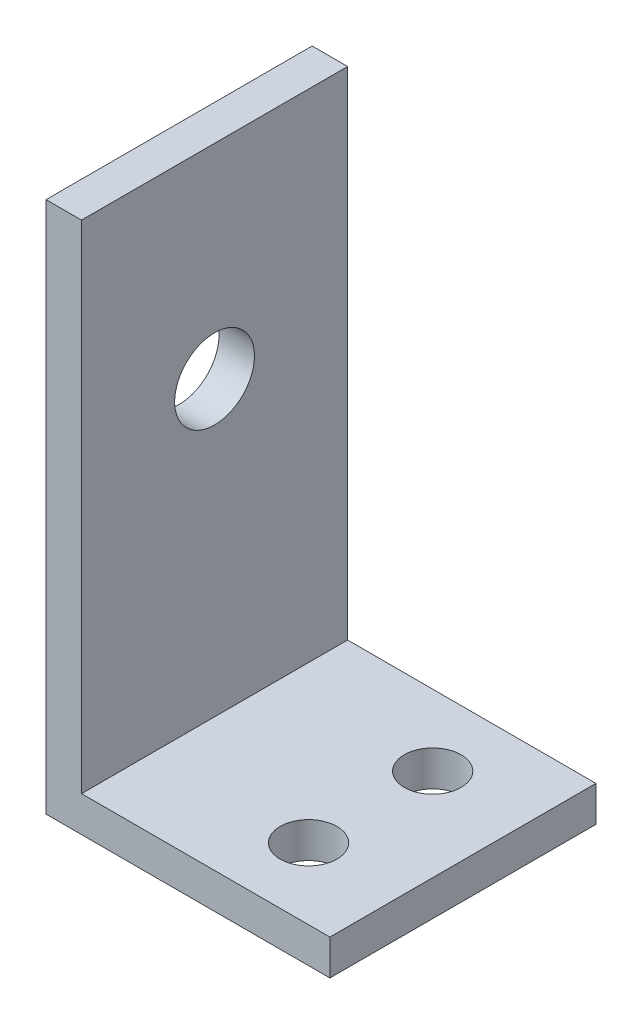
SolidWorks part; units mm, degrees
ref_plane "Front Plane" through (0, 0, 0) normal (0, 0, 1) x (1, 0, 0)
ref_plane "Top Plane" through (0, 0, 0) normal (0, 1, 0) x (1, 0, 0)
ref_plane "Right Plane" through (0, 0, 0) normal (1, 0, 0) x (0, 0, -1)
sketch "Sketch1" plane through (0, 0, 0) normal (0, 1, 0) x (1, 0, 0)
  line L1 (-3.8235, 10.0882) -> (12.1765, 10.0882)
  line L2 (-3.8235, 10.0882) -> (-3.8235, -4.9118)
  line L3 (-3.8235, -4.9118) -> (12.1765, -4.9118)
  line L4 (12.1765, 10.0882) -> (12.1765, -4.9118)
  dimension "D1" = 16
  dimension "D2" = 15
extrude "Boss-Extrude1" add sketch "Sketch1" along normal blind 2
sketch "Sketch4" plane through (0, 2, 0) normal (0, 1, 0) x (1, 0, 0)
  line L0 (12.1765, 10.0882) -> (-3.8235, 10.0882) construction
  line L1 (-3.8235, -4.9118) -> (-1.8235, -4.9118)
  line L2 (-3.8235, -4.9118) -> (-3.8235, 10.0882)
  line L3 (-3.8235, 10.0882) -> (-1.8235, 10.0882)
  line L4 (-1.8235, -4.9118) -> (-1.8235, 10.0882)
  dimension "D1" = 2
extrude "Boss-Extrude4" add sketch "Sketch4" along normal blind 28
hole_wizard "Ø3.2 (3.2) Diameter Slot1" positions "Sketch9" profile "Sketch7" size "Ø3.2" standard "ANSI Metric" slot yes end condition through all
sketch "Sketch9" plane through (0, 2, 0) normal (0, 1, 0) x (1, 0, 0)
  line L1 (12.1765, 10.0882) -> (-1.8235, 10.0882) construction
  line L2 (-1.8235, -4.9118) -> (12.1765, -4.9118) construction
  point P0 (6.9728, 6.0882)
  point P2 (6.9728, -0.9118)
  point P12 (5.1765, -4.9118)
  dimension "D1" = 4
  dimension "D2" = 4
sketch "Sketch7" plane through (6.9728, 2, -6.0882) normal (1, 0, 0) x (0, 0, 1)
  line L0 (0, 0) -> (0, 2)
  line L1 (0, 2) -> (1.6, 2)
  line L2 (1.6, 2) -> (1.6, 0)
  line L5 (1.6, 0) -> (0, 0)
  line L11 (0, -6.35) -> (0, 107.95) construction
  dimension "Thru Hole Dia." = 3.2
  dimension "Thru Hole Depth" = 2
hole_wizard "M4 Clearance Slot1" positions "Sketch12" profile "Sketch13" size "M4" standard "ANSI Metric" slot yes end condition through all
sketch "Sketch12" plane through (-1.8235, 0, 0) normal (1, 0, 0) x (0, 0, -1)
  line L0 (10.0882, 30) -> (10.0882, 2) construction
  line L1 (-4.9118, 30) -> (10.0882, 30) construction
  point P0 (2.5882, 18.5)
  dimension "D1" = 7.5
  dimension "D2" = 11.5
sketch "Sketch13" plane through (-1.8235, 18.5, -2.5882) normal (0, 1, 0) x (0, 0, -1)
  line L0 (0, 0) -> (0, 2)
  line L1 (0, 2) -> (2.25, 2)
  line L2 (2.25, 2) -> (2.25, 0)
  line L5 (2.25, 0) -> (0, 0)
  line L11 (0, -6.35) -> (0, 107.95) construction
  dimension "Thru Hole Dia." = 4.5
  dimension "Thru Hole Depth" = 2
